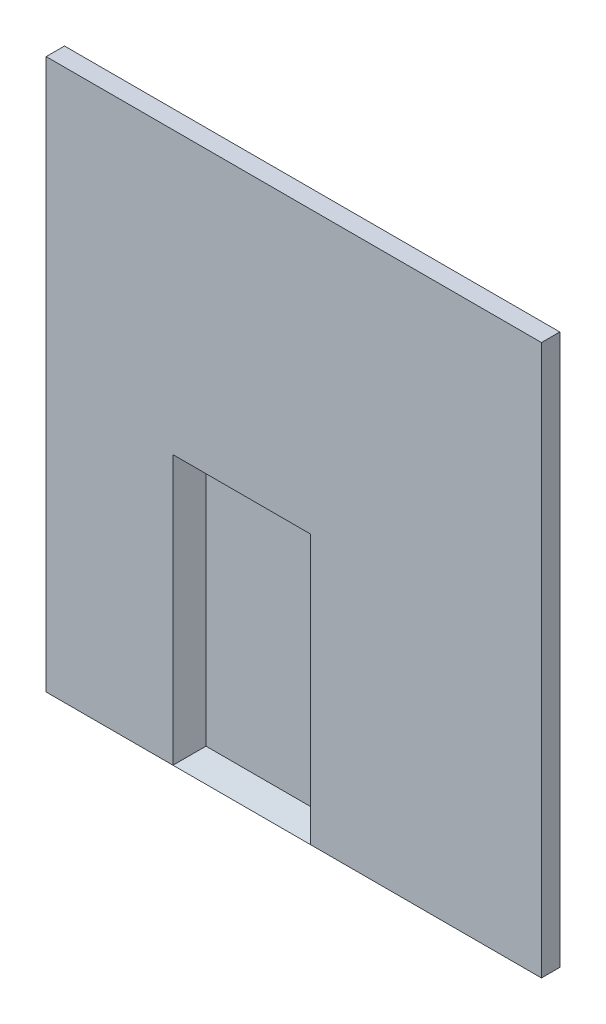
SolidWorks part; units mm, degrees
ref_plane "Front Plane" through (0, 0, 0) normal (0, 0, 1) x (1, 0, 0)
ref_plane "Top Plane" through (0, 0, 0) normal (0, 1, 0) x (1, 0, 0)
ref_plane "Right Plane" through (0, 0, 0) normal (1, 0, 0) x (0, 0, -1)
sketch "Sketch1" plane through (0, 0, 0) normal (0, 0, 1) x (1, 0, 0)
  line L1 (135, -150) -> (-135, -150)
  line L2 (135, -150) -> (135, 150)
  line L3 (135, 150) -> (-135, 150)
  line L4 (-135, -150) -> (-135, 150)
  line L5 (135, -150) -> (-135, 150) construction
  line L6 (135, 150) -> (-135, -150) construction
  point P0 (0, 0)
extrude "Boss-Extrude1" add sketch "Sketch1" along normal blind 10 contours L2 L1 L4 L3
sketch "Sketch2" plane through (0, 0, 10) normal (0, 0, 1) x (1, 0, 0)
  line L1 (135, -150) -> (-135, -150) construction
  line L3 (-65.89, -150) -> (9.11, -150)
  line L4 (-65.89, -150) -> (-65.89, -3.35)
  line L5 (-65.89, -3.35) -> (9.11, -3.35)
  line L6 (9.11, -150) -> (9.11, -3.35)
extrude "Cut-Extrude1" cut sketch "Sketch2" against normal blind 9 draft 45
